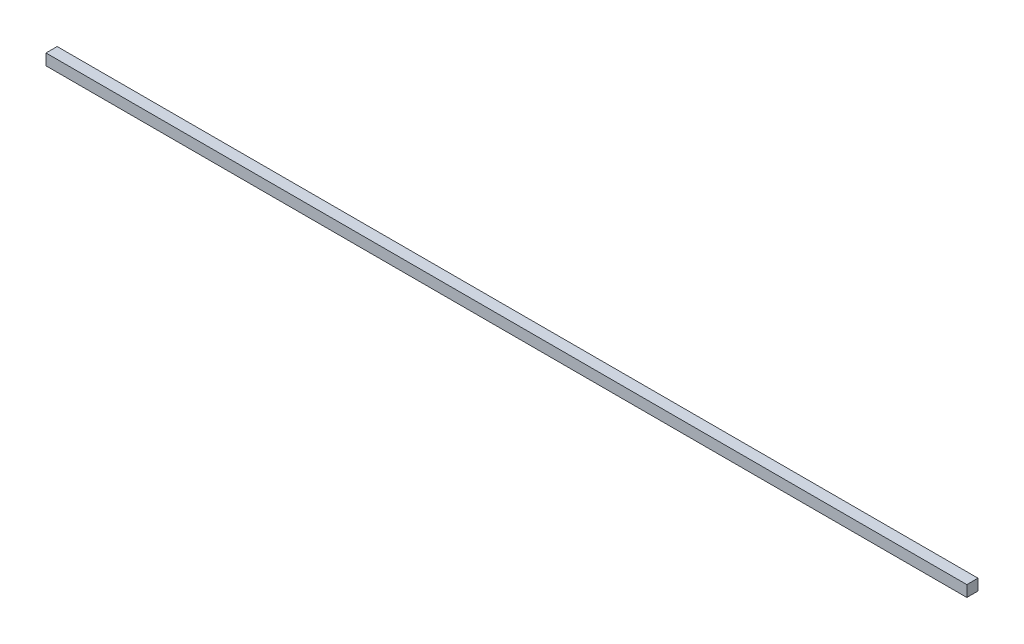
SolidWorks part; units mm, degrees
ref_plane "Front Plane" through (0, 0, 0) normal (0, 0, 1) x (1, 0, 0)
ref_plane "Top Plane" through (0, 0, 0) normal (0, 1, 0) x (1, 0, 0)
ref_plane "Right Plane" through (0, 0, 0) normal (1, 0, 0) x (0, 0, -1)
other "Configuration Table"
sketch "Sketch1" plane through (0, 0, 0) normal (0, 0, 1) x (1, 0, 0)
  line L1 (-10, 2) -> (650, 2)
  line L2 (-10, 2) -> (-10, 10)
  line L3 (-10, 10) -> (650, 10)
  line L4 (650, 2) -> (650, 10)
extrude "FKAP_pivot_mili_D8_1" add sketch "Sketch1" along normal blind 8 from offset 26 separate body
